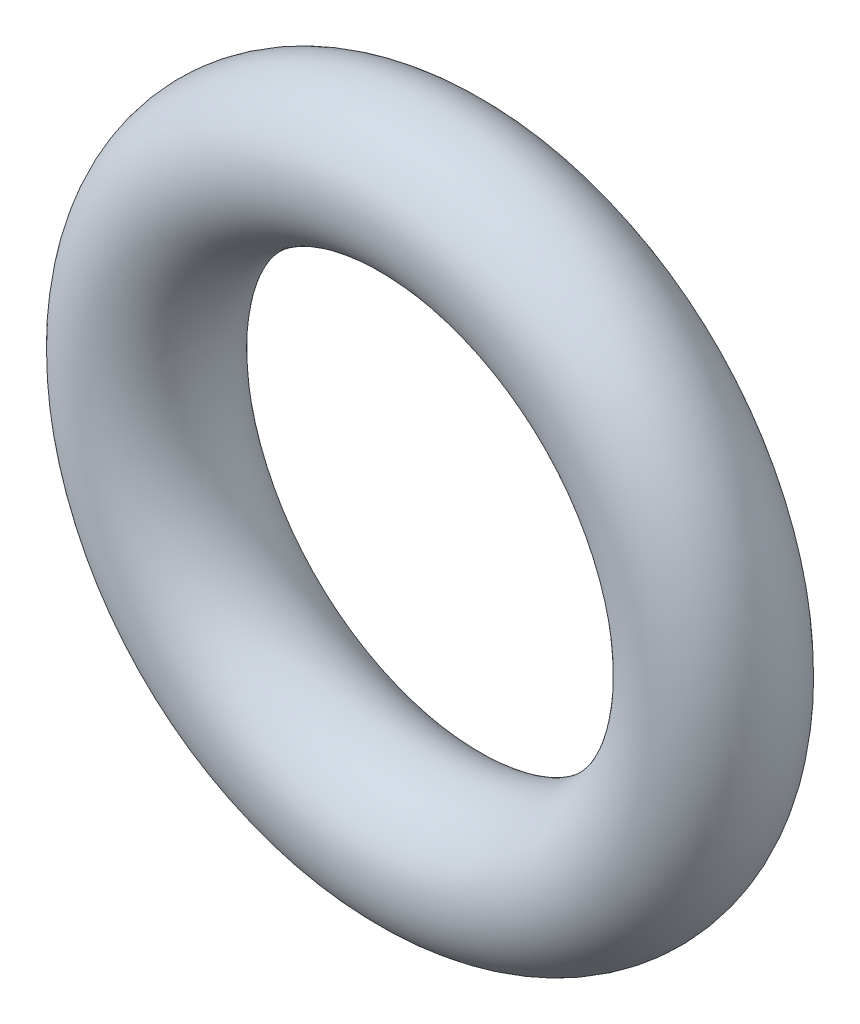
SolidWorks part; units mm, degrees
ref_plane "Front Plane" through (0, 0, 0) normal (0, 0, 1) x (1, 0, 0)
ref_plane "Top Plane" through (0, 0, 0) normal (0, 1, 0) x (1, 0, 0)
ref_plane "Right Plane" through (0, 0, 0) normal (1, 0, 0) x (0, 0, -1)
ref_plane "plane:profile-xz" through (0, 0, 0) normal (0, -1, 0) x (1, 0, 0)
sketch "sketch:main-profile" plane through (0, 0, 0) normal (0, -1, 0) x (1, 0, 0)
  line L0 (0, -15) -> (0, 15) construction
  circle A0 centre (20, 0) radius 5
revolve "feature:torus" add sketch "sketch:main-profile" angle 360 about L0
